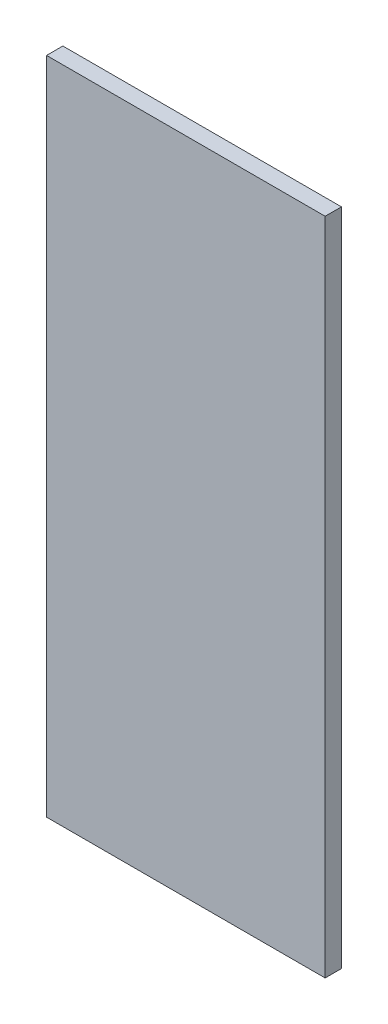
SolidWorks part; units mm, degrees
ref_plane "Front Plane" through (0, 0, 0) normal (0, 0, 1) x (1, 0, 0)
ref_plane "Top Plane" through (0, 0, 0) normal (0, 1, 0) x (1, 0, 0)
ref_plane "Right Plane" through (0, 0, 0) normal (1, 0, 0) x (0, 0, -1)
sketch "Sketch1" plane through (0, 0, 0) normal (0, 0, 1) x (1, 0, 0)
  line L1 (334.3356, 0) -> (160.5887, 0)
  line L2 (334.3356, 0) -> (334.3356, -411.4306)
  line L3 (334.3356, -411.4306) -> (160.5887, -411.4306)
  line L4 (160.5887, 0) -> (160.5887, -411.4306)
extrude "Boss-Extrude1" add sketch "Sketch1" along normal blind 10.16
